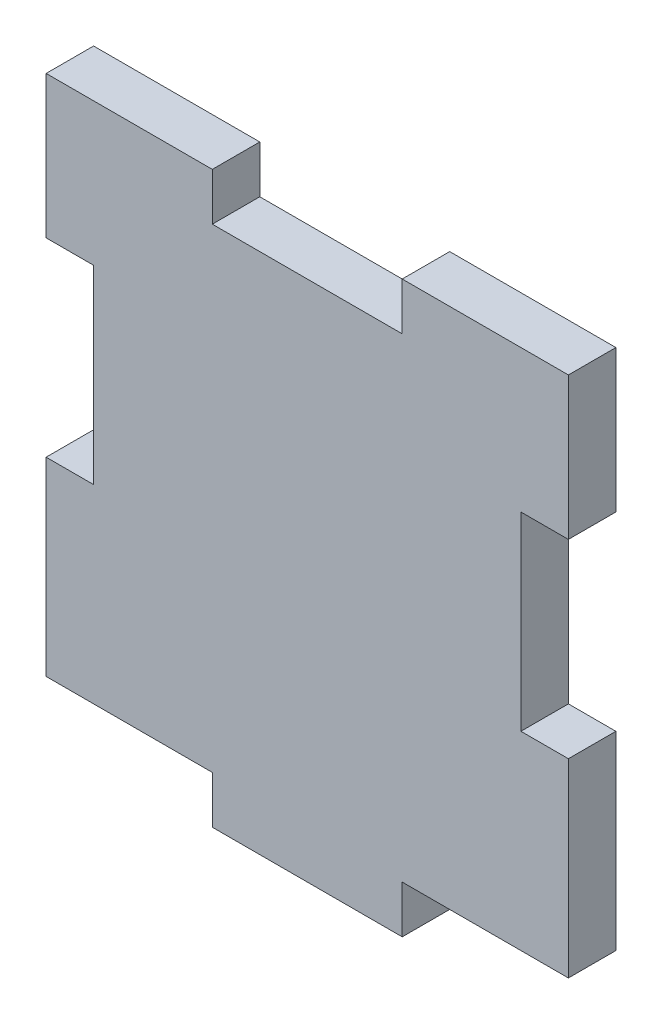
SolidWorks part; units mm, degrees
ref_plane "Front Plane" through (0, 0, 0) normal (0, 0, 1) x (1, 0, 0)
ref_plane "Top Plane" through (0, 0, 0) normal (0, 1, 0) x (1, 0, 0)
ref_plane "Right Plane" through (0, 0, 0) normal (1, 0, 0) x (0, 0, -1)
sketch "Sketch1" plane through (0, 0, 0) normal (0, 0, 1) x (1, 0, 0)
  line L0 (0, 6.35) -> (22.225, 6.35)
  line L1 (22.225, 6.35) -> (22.225, 0)
  line L2 (22.225, 0) -> (47.625, 0)
  line L3 (47.625, 0) -> (47.625, 6.35)
  line L4 (47.625, 6.35) -> (69.85, 6.35)
  line L5 (69.85, 6.35) -> (69.85, 31.75)
  line L6 (69.85, 76.2) -> (47.625, 76.2)
  line L7 (0, 76.2) -> (0, 57.15)
  line L8 (0, 6.35) -> (0, 0) construction
  line L9 (0, 0) -> (22.225, 0) construction
  line L10 (34.925, 0) -> (34.925, 76.2) construction
  line L11 (0, 57.15) -> (6.35, 57.15)
  line L12 (6.35, 57.15) -> (6.35, 31.75)
  line L13 (6.35, 31.75) -> (0, 31.75)
  line L14 (0, 31.75) -> (0, 6.35)
  line L15 (22.225, 76.2) -> (22.225, 69.85)
  line L16 (22.225, 69.85) -> (47.625, 69.85)
  line L17 (47.625, 69.85) -> (47.625, 76.2)
  line L18 (22.225, 76.2) -> (0, 76.2)
  line L19 (22.225, 76.2) -> (47.625, 76.2) construction
  line L20 (69.85, 57.15) -> (63.5, 57.15)
  line L21 (63.5, 57.15) -> (63.5, 31.75)
  line L22 (63.5, 31.75) -> (69.85, 31.75)
  line L23 (69.85, 57.15) -> (69.85, 76.2)
  point P20 (34.925, 69.85)
  dimension "D1" = 25.4
  dimension "D2" = 6.35
  dimension "D3" = 69.85
  dimension "D4" = 69.85
  dimension "D5" = 6.35
  dimension "D6" = 25.4
  dimension "D7" = 25.4
  dimension "D8" = 25.4
  dimension "D9" = 6.35
  dimension "D10" = 34.925
  dimension "D11" = 6.35
extrude "Extrude1" add sketch "Sketch1" along normal blind 6.35
